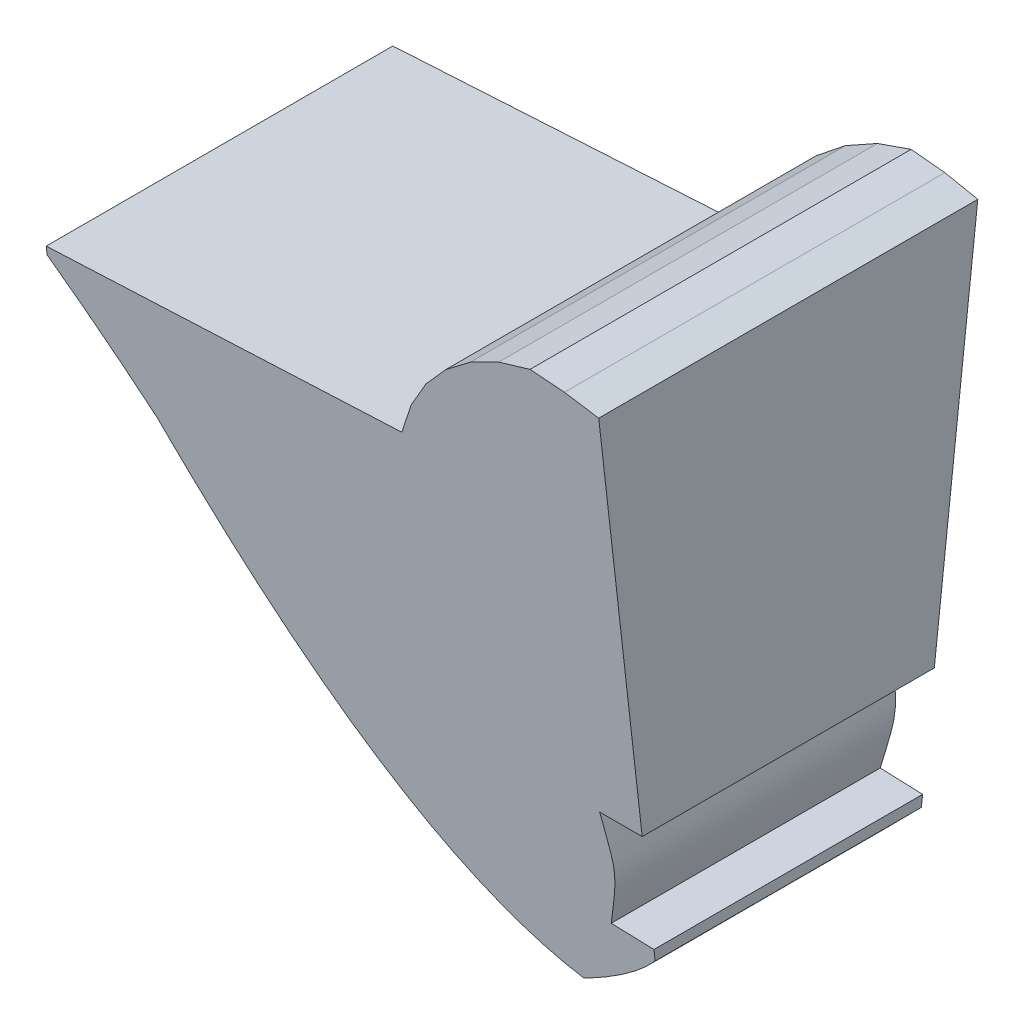
SolidWorks part; units mm, degrees
ref_plane "Alzado" through (0, 0, 0) normal (0, 0, 1) x (1, 0, 0)
ref_plane "Planta" through (0, 0, 0) normal (0, 1, 0) x (1, 0, 0)
ref_plane "Vista lateral" through (0, 0, 0) normal (1, 0, 0) x (0, 0, -1)
sketch "Croquis1" plane through (0, 0, 0) normal (0, 0, 1) x (1, 0, 0)
  line L0 (-8.9818, 12.6082) -> (-23.0359, 11.8716) construction
  line L1 (-8.9818, 12.6082) -> (-23.0359, 11.8716)
  line L2 (-8.9818, 12.6082) -> (-23.0359, 11.8716) construction
  line L4 (-8.9818, 12.6082) -> (-23.0359, 11.8716)
  line L6 (-1.3949, 1.9763) -> (0.3551, 2.2848) construction
  line L7 (-1.3949, 1.9763) -> (0.3551, 2.2848)
  line L8 (0.3551, 2.2848) -> (0.3551, 2.8423) construction
  line L9 (0.3551, 2.2848) -> (0.3551, 3.0015)
  line L10 (0.3551, -2.2848) -> (-1.3949, -2.2237) construction
  line L11 (0.3551, -2.2848) -> (-1.3949, -2.2237)
  line L12 (0.3551, 2.2848) -> (0.3551, -2.2848) construction
  line L13 (0.3551, -2.2848) -> (0.3551, -2.7233)
  line L14 (-8.9818, 12.6082) -> (-6.9949, 10.4774)
  line L15 (-23.0359, 11.5401) -> (-23.0359, 11.8716) construction
  line L16 (-23.0359, 11.5401) -> (-23.0359, 11.8716)
  arc A0 (-18.9452, 7.5409) -> (-23.0359, 11.5401) centre (-69.8841, -40.4718) ccw construction
  arc A1 (-18.9452, 7.5409) -> (-23.0359, 11.5401) centre (-69.8841, -40.4718) ccw
  spline S1 degree 2 poles (-828.7061, 3922.2202) (545.889, -3962.7836) (-262.0834, 3982.5902) knots 0.462185 0.462185 0.462185 0.537731 0.537731 0.537731 weights 1 1 1 only from (-18.9452, 7.5409) to (-2.8466, -5.0591) construction
  spline S2 degree 2 poles (-18.9452, 7.5409) (-10.215, -3.6976) (-2.8466, -5.0591) knots 0.497667 0.497667 0.497667 0.499554 0.499554 0.499554 weights 1 1 1
  spline S3 degree 2 poles (-3804.8689, 1232.5771) (3762.9122, -1369.6643) (-3716.5752, 1504.852) knots 0.462212 0.462212 0.462212 0.537836 0.537836 0.537836 weights 1 1 1 only from (0.3551, 3.0015) to (-6.9949, 10.4774) construction
  spline S4 degree 2 poles (0.3551, 3.0015) (-1.4487, 6.0584) (-6.9949, 10.4774) knots 0.500821 0.500821 0.500821 0.502013 0.502013 0.502013 weights 1 1 1
  spline S5 degree 2 poles (-1.3949, -2.2237) (-0.9075, -0.1237) (-1.3949, 1.9763) knots 0 0 0 1 1 1 weights 1 3.231801 1 construction
  spline S6 degree 2 poles (-1.3949, -2.2237) (-0.9075, -0.1237) (-1.3949, 1.9763) knots 0 0 0 1 1 1 weights 1 3.231801 1
  spline S7 degree 2 poles (-3997.263, 185.0077) (3984.2333, -348.7483) (-3965.0625, 511.2595) knots 0.462205 0.462205 0.462205 0.537778 0.537778 0.537778 weights 1 1 1 only from (-2.8466, -5.0591) to (0.3551, -2.7233) construction
  spline S8 degree 2 poles (-2.8466, -5.0591) (-0.7424, -3.9352) (0.3551, -2.7233) knots 0.498812 0.498812 0.498812 0.499413 0.499413 0.499413 weights 1 1 1
extrude "Saliente-Extruir1" add sketch "Croquis1" along normal mid plane 14.42 contours S2 S8 L13 L11 S6 L7 L9 S4 L14 L1 L16 A1
sketch "Croquis3" plane through (0, 0, 0) normal (0, 0, 1) x (1, 0, 0)
  line L0 (-6.742, 0) -> (0, 0) construction
  line L1 (-1.8181, 2) -> (-1.7771, 2.0103) construction
  line L3 (-1.8181, 2) -> (-0.1689, 2.4155) construction
  line L4 (-1.8181, 2) -> (0.3551, 3.0015)
  line L5 (0.3551, 3.0015) -> (0.3551, 0)
  line L6 (-1.9112, -2.1782) -> (0.3551, -2.2848)
  line L7 (0.3551, -2.2848) -> (0.3551, 0)
  parabola Q0 (-1.9112, -2.1782) -> (-1.8181, 2) focus (-3.3181, 0) apex (-1.3181, 0)
  dimension "D1" = 2
  dimension "D2" = 2
extrude "Cortar-Extruir1" [suppressed] cut sketch "Croquis3" against normal through all both and the other way through all
sketch "Croquis4" plane through (0, 0, 0) normal (0, 0, 1) x (1, 0, 0)
  line L0 (-1.3949, 1.9763) -> (0.3551, 2.2848) construction
  line L1 (-1.3949, 1.9763) -> (0.3551, 2.2848)
  line L2 (0.3551, 2.2848) -> (0.3551, 3.0015) construction
  line L3 (0.3551, 1.9763) -> (0.3551, 2.2848)
  line L4 (-1.3949, 1.9763) -> (0.3551, 1.9763)
  line L5 (0, 0) -> (-3.4665, 0) construction
  dimension "D1" = 0
extrude "Saliente-Extruir2" add sketch "Croquis4" along normal through all and the other way through all
sketch "Croquis7" plane through (0, 0, 0) normal (0, 0, 1) x (1, 0, 0)
  line L0 (0, 0) -> (-13.2475, 1.1183) construction
  line L1 (-14.9286, 14.3063) -> (-13.2475, 1.1183) construction
  line L2 (-13.2475, 1.1183) -> (-7.4174, -4.4688) construction
  line L3 (-13.2475, 1.1183) -> (-8.4034, 6.1732) construction
  line L4 (-14.9286, 14.3063) -> (-14.7, 12.5132) construction
  line L5 (0, 0) -> (-1.3461, -2.2254) construction
  line L6 (-69.8841, 29.5282) -> (-81.9382, 42.5765) construction
  line L7 (-69.8841, 29.5282) -> (-20.9497, 29.5282) construction
  line L8 (-17.8101, 13.1658) -> (-25.5429, 13.1658)
  line L9 (-17.6007, 6.3083) -> (-21.9246, 11.9299) construction
  line L10 (0.3551, -2.5) -> (-2.4497, -2.0473)
  line L11 (-1.3461, -2.2254) -> (-2.0075, -3.6222) construction
  line L12 (-1.3461, -2.2254) -> (-1.4547, -2.8987) construction
  line L13 (-1.3461, -2.2254) -> (-1.2286, -1.4976) construction
  line L14 (0.3551, -2.2848) -> (0.3551, -2.7233) construction
  line L15 (0.3551, -2.2848) -> (-1.3949, -2.2237) construction
  line L16 (-2.0075, -3.6222) -> (-2.6381, -4.9541) construction
  line L17 (-2.6331, -4.9434) -> (-3.7044, -5.5324) construction
  line L18 (-2.6331, -4.9434) -> (-3.2248, -3.867) construction
  line L19 (-2.6331, -4.9434) -> (-2.2174, -6.1341) construction
  line L20 (-4.0838, -4.7637) -> (-2.6213, -4.9448) construction
  line L21 (-4.0838, -4.7637) -> (-0.036, -5.9454) construction
  line L22 (-4.0838, -4.7637) -> (-3.7621, -3.6616) construction
  line L23 (-4.0838, -4.7637) -> (-5.4141, -4.1295) construction
  line L24 (-5.4141, -4.1295) -> (-8.69, -2.5677) construction
  line L25 (-8.69, -2.5677) -> (-6.8421, -3.7725) construction
  line L26 (-8.69, -2.5677) -> (-7.9481, -1.4297) construction
  line L27 (-11.4407, -0.2002) -> (-8.69, -2.5677) construction
  line L28 (-11.4407, -0.2002) -> (-14.8546, 2.738) construction
  line L29 (-14.8546, 2.738) -> (-14.5337, 2.3989) construction
  line L30 (-14.8546, 2.738) -> (-14.6199, 2.9602) construction
  line L31 (-17.6007, 6.3083) -> (-14.8546, 2.738) construction
  line L32 (-8.9818, 12.6082) -> (-23.0359, 11.8716) construction
  line L33 (-8.9818, 12.6082) -> (-23.0359, 11.8716)
  line L34 (-21.9246, 11.9299) -> (-21.9826, 13.0367) construction
  line L35 (-21.9246, 11.9299) -> (-23.4156, 13.0367) construction
  arc A0 (-18.9452, 7.5409) -> (-23.0359, 11.5401) centre (-69.8841, -40.4718) ccw construction
  spline S0 degree 2 poles (-828.7061, 3922.2202) (545.889, -3962.7836) (-262.0834, 3982.5902) knots 0.462185 0.462185 0.462185 0.537731 0.537731 0.537731 weights 1 1 1 only from (-18.9452, 7.5409) to (-2.8466, -5.0591) construction
  spline S1 degree 2 poles (-18.6263, 7.1332) (-10.0803, -3.7225) (-2.8466, -5.0591) knots 0.497702 0.497702 0.497702 0.499554 0.499554 0.499554 weights 1 1 1 construction
  spline S3 degree 2 poles (-3997.263, 185.0077) (3984.2333, -348.7483) (-3965.0625, 511.2595) knots 0.462205 0.462205 0.462205 0.537778 0.537778 0.537778 weights 1 1 1 only from (-2.8466, -5.0591) to (0.3551, -2.7233) construction
  spline S4 degree 2 poles (-2.8466, -5.0591) (-2.7385, -5.0013) (-2.6331, -4.9434) knots 0.498812 0.498812 0.498812 0.498843 0.498843 0.498843 weights 1 1 1
  dimension "D1" = 2.5
  dimension "D2" = 22
  dimension "D3" = 16.17
  dimension "D4" = 54.138
  dimension "D5" = 34.566
  dimension "D6" = 50.413
sketch "Croquis6" plane through (0, 0, 0) normal (1, 0, 0) x (0, 0, -1)
  line L0 (7.21, 12.6082) -> (7.21, 10.4774) construction
  line L1 (7.21, 12.6082) -> (7.21, -5.0591)
  line L2 (-7.21, 12.6082) -> (-7.21, 10.4774) construction
  line L3 (-7.21, 12.6082) -> (-7.21, -5.0591)
  line L4 (-7.21, -5.0591) -> (7.21, -5.0591) construction
  line L5 (-7.21, -5.0591) -> (-5.21, -5.0591)
  line L6 (7.21, 12.6082) -> (5.21, -5.0591)
  line L7 (-7.21, 12.6082) -> (-5.21, -5.0591)
  line L8 (5.21, -5.0591) -> (7.21, -5.0591)
  dimension "D1" = 2
  dimension "D2" = 2
extrude "Cortar-Extruir2" cut sketch "Croquis6" against normal through all and the other way through all
sketch "Croquis8" plane through (0, 0, 0) normal (0, 0, 1) x (1, 0, 0)
  line L0 (-8.9818, 12.6082) -> (-23.0359, 11.8716) construction
  line L1 (-9.7264, 12.5691) -> (0.3551, 17.7735) construction
  line L2 (0.3551, 1.9763) -> (0.3551, 3.0015) construction
  line L3 (0.3551, 3.0015) -> (0.3551, 17.7735)
  line L5 (-8.3233, 12.6427) -> (-7.797, 13.9454)
  line L6 (-7.797, 13.9454) -> (-7.0524, 15.1369)
  line L7 (-7.0524, 15.1369) -> (-6.1123, 16.1811)
  line L8 (-6.1123, 16.1811) -> (-5.0051, 17.0461)
  line L9 (-5.0051, 17.0461) -> (-3.7645, 17.7057)
  line L10 (-3.7645, 17.7057) -> (-2.4283, 18.1399)
  line L11 (-2.4283, 18.1399) -> (-1.0286, 18.0174)
  line L12 (-1.0286, 18.0174) -> (0.3551, 17.7735)
  line L13 (-0.5199, 1.9763) -> (-9.282, 12.9915) construction
  line L14 (-9.282, 12.9915) -> (-9.6919, 13.4229) construction
  line L15 (-9.282, 12.9915) -> (-9.8512, 13.838) construction
  line L16 (-0.5199, 1.9763) -> (-8.0602, 13.294) construction
  line L17 (-8.0602, 13.294) -> (-9.1208, 13.7226) construction
  line L18 (-0.5199, 1.9763) -> (-7.4247, 14.5412) construction
  line L19 (0.3551, 1.9763) -> (-1.3949, 1.9763) construction
  line L20 (-7.4247, 14.5412) -> (-7.564, 14.6282) construction
  line L21 (-0.5199, 1.9763) -> (-6.5824, 15.659) construction
  line L22 (-0.5199, 1.9763) -> (-5.5587, 16.6136) construction
  line L23 (-5.5587, 16.6136) -> (-6.1777, 17.4058) construction
  line L24 (-0.5199, 1.9763) -> (-4.3848, 17.3759) construction
  line L25 (-4.3848, 17.3759) -> (-4.7166, 18) construction
  line L26 (-0.5199, 1.9763) -> (-3.0964, 17.9228) construction
  line L27 (-3.0964, 17.9228) -> (-3.34, 18.6726) construction
  line L28 (-0.5199, 1.9763) -> (-1.7284, 18.0787) construction
  line L29 (-1.7284, 18.0787) -> (-1.7309, 18.0503) construction
  line L30 (-0.5199, 1.9763) -> (-0.3367, 17.8955) construction
  line L31 (-0.3367, 17.8955) -> (-0.4834, 17.0639) construction
  line L32 (-7.4247, 14.5412) -> (-8.2283, 15.0433) construction
  line L33 (-6.5824, 15.659) -> (-7.2613, 16.2703) construction
  line L34 (-9.7264, 12.5691) -> (-9.7264, 19.4167) construction
  line L35 (-0.3367, 17.8955) -> (-0.2962, 18.1254) construction
  line L36 (-9.7264, 12.5691) -> (-8.3233, 12.6427)
  line L37 (-8.0602, 13.294) -> (-8.3005, 14.335) construction
  line L38 (-8.0602, 13.294) -> (-6.9403, 12.8416) construction
  line L39 (-7.4247, 14.5412) -> (-7.8205, 16.2557) construction
  line L40 (-7.4247, 14.5412) -> (-7.159, 14.3751) construction
  line L41 (-6.5824, 15.659) -> (-6.8504, 16.8201) construction
  line L42 (-6.5824, 15.659) -> (-6.1207, 15.2433) construction
  line L43 (-5.5587, 16.6136) -> (-6.0278, 18.6457) construction
  line L44 (-5.5587, 16.6136) -> (-5.0299, 15.9367) construction
  line L45 (-4.3848, 17.3759) -> (-4.8775, 19.5099) construction
  line L46 (-4.3848, 17.3759) -> (-4.0664, 16.7772) construction
  line L47 (-3.0964, 17.9228) -> (-3.5544, 19.9066) construction
  line L48 (-3.0964, 17.9228) -> (-2.7244, 16.7779) construction
  spline S0 degree 2 poles (-1851.9698, 781.7085) (1883.9916, -685.7524) (-1911.5868, 588.043) knots 0.476049 0.476049 0.476049 0.529551 0.529551 0.529551 weights 1 1 1 only from (-6.9949, 10.4774) to (0.3551, 3.0015) construction
  spline S1 degree 2 poles (-9.7264, 12.5691) (-1.8611, 6.7573) (0.3551, 3.0015) knots 0.500548 0.500548 0.500548 0.502013 0.502013 0.502013 weights 1 1 1
  point P6 (-2.7242, 16.7772)
  point P50 (-2.4283, 18.1254)
  point P52 (-2.4283, 18.1254)
  point P54 (-2.4283, 18.1254)
  point P56 (-2.4283, 18.1254)
  dimension "D1" = 5.039
  dimension "D2" = 95
  dimension "D3" = 15
  dimension "D4" = 25
  dimension "D5" = 80
  dimension "D6" = 45
  dimension "D7" = 35
  dimension "D8" = 5
  dimension "D9" = 100
  dimension "D10" = 55
  dimension "D11" = 34.327
  dimension "D12" = 29.21
  dimension "D13" = 24.103
  dimension "D14" = 19.004
  dimension "D15" = 13.911
extrude "Saliente-Extruir3" add sketch "Croquis8" along normal up to surface and the other way up to surface up to face at (-6.8548, 3.8413, 6.2176) other way up to face at (-6.9269, 3.652, -6.1961)
